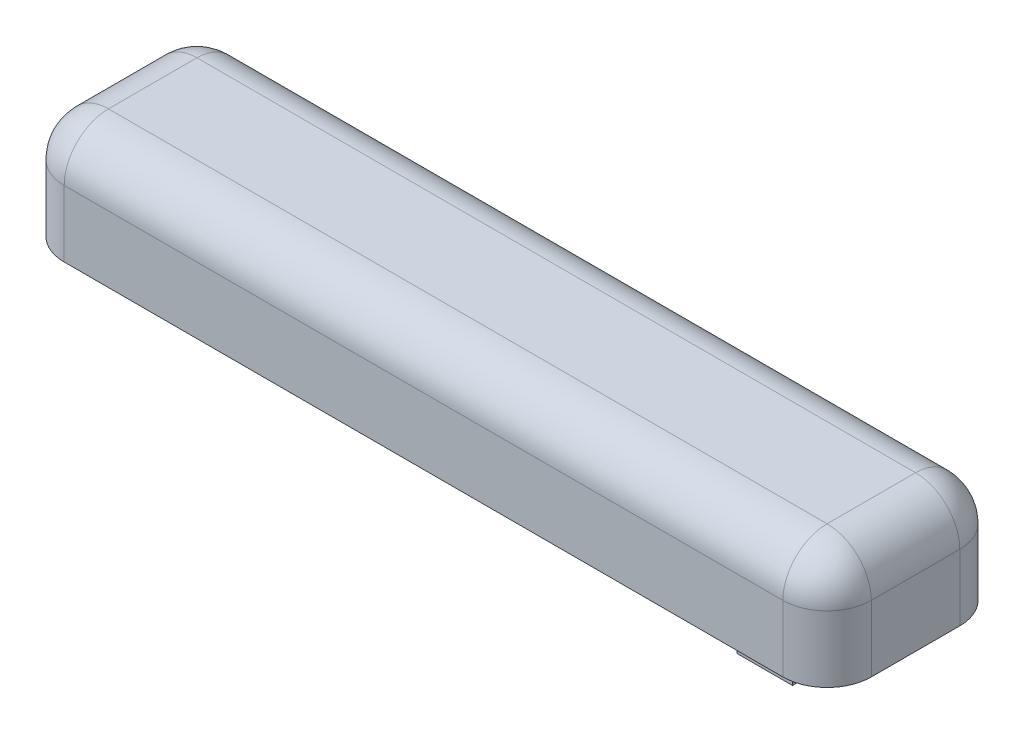
SolidWorks part; units mm, degrees
ref_plane "Alzado" through (0, 0, 0) normal (0, 0, 1) x (1, 0, 0)
ref_plane "Planta" through (0, 0, 0) normal (0, 1, 0) x (1, 0, 0)
ref_plane "Vista lateral" through (0, 0, 0) normal (1, 0, 0) x (0, 0, -1)
sketch "Croquis1" plane through (0, 0, 0) normal (0, 1, 0) x (1, 0, 0)
  line L1 (0, 0) -> (-365, 0)
  line L2 (0, 0) -> (0, 80)
  line L3 (0, 80) -> (-365, 80)
  line L4 (-365, 0) -> (-365, 80)
  dimension "D1" = 365
  dimension "D2" = 80
extrude "Saliente-Extruir1" add sketch "Croquis1" along normal blind 50 contours L2 L1 L4 L3
fillet "Redondeo1" radius 20 1 edges at (-182.5, 50, -80)
fillet "Redondeo2" radius 20 1 edges at (-182.5, 50, 0)
fillet "Redondeo3" radius 20 5 edges at (0, 15, 0) (0, 44.1421, -5.8579) (0, 15, -80) (0, 44.1421, -74.1421) (0, 50, -40)
fillet "Redondeo4" radius 20 5 edges at (-365, 15, 0) (-365, 44.1421, -5.8579) (-365, 15, -80) (-365, 44.1421, -74.1421) (-365, 50, -40)
sketch "Croquis2" plane through (0, 0, 0) normal (0, -1, 0) x (1, 0, 0)
  line L5 (-66.4672, -25.8166) -> (-41.4672, -25.8166)
  line L6 (-66.4672, -25.8166) -> (-66.4672, -50.8166)
  line L7 (-66.4672, -50.8166) -> (-41.4672, -50.8166)
  line L8 (-41.4672, -25.8166) -> (-41.4672, -50.8166)
  dimension "D1" = 25
  dimension "D2" = 25
extrude "Saliente-Extruir2" add sketch "Croquis2" along normal blind 27
sketch "Croquis3" plane through (0, -27, 0) normal (0, -1, 0) x (1, 0, 0)
  line L1 (-63.5, -47.5) -> (-44.5, -47.5)
  line L2 (-63.5, -47.5) -> (-63.5, -28.5)
  line L3 (-63.5, -28.5) -> (-44.5, -28.5)
  line L4 (-44.5, -47.5) -> (-44.5, -28.5)
  line L5 (-63.5, -47.5) -> (-44.5, -28.5) construction
  line L6 (-63.5, -28.5) -> (-44.5, -47.5) construction
  point P0 (-54, -38)
  point P5 (0, 0)
  dimension "D1" = 19
  dimension "D2" = 19
extrude "Cortar-Extruir1" cut sketch "Croquis3" against normal blind 23
